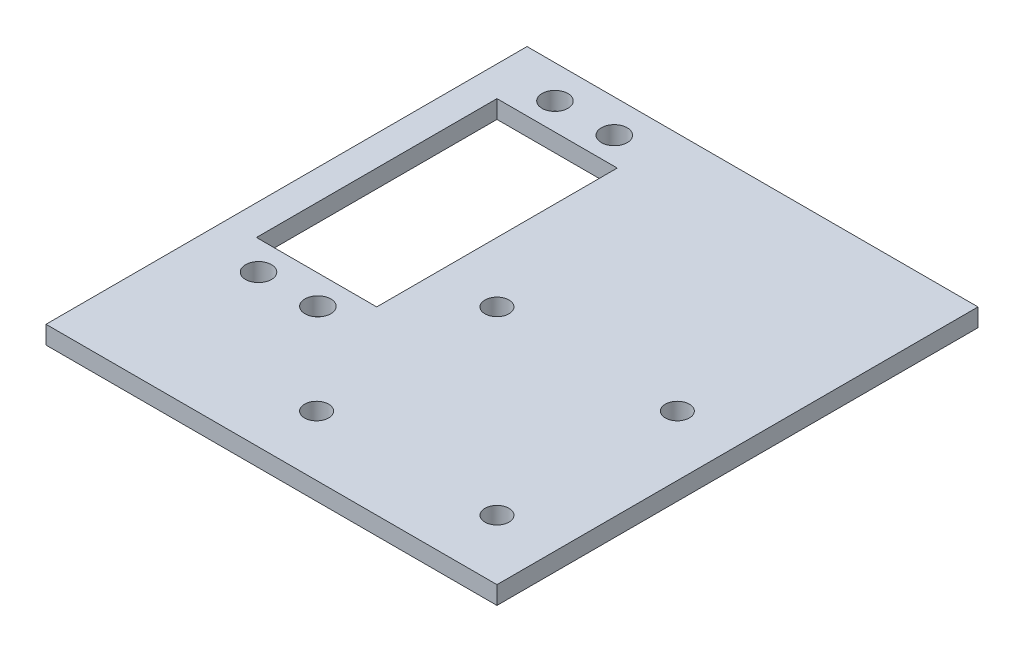
SolidWorks part; units mm, degrees
ref_plane "Front Plane" through (0, 0, 0) normal (0, 0, 1) x (1, 0, 0)
ref_plane "Top Plane" through (0, 0, 0) normal (0, 1, 0) x (1, 0, 0)
ref_plane "Right Plane" through (0, 0, 0) normal (1, 0, 0) x (0, 0, -1)
sketch "Sketch2" plane through (0, 0, 0) normal (0, 1, 0) x (1, 0, 0)
  line L1 (-40, -40) -> (40, -40)
  line L2 (-40, -40) -> (-40, 40)
  line L3 (-40, 40) -> (40, 40)
  line L4 (40, -40) -> (40, 40)
  line L5 (0, 40) -> (0, -40) construction
  line L6 (-40, 0) -> (40, 0) construction
  point P0 (0, 0)
  dimension "D1" = 80
  dimension "D2" = 80
extrude "Boss-Extrude1" add sketch "Sketch2" along normal blind 3
sketch "Sketch3" plane through (0, 3, 0) normal (0, 1, 0) x (1, 0, 0)
  line L0 (-35, 35) -> (-35, 40) construction
  line L2 (-40, 35) -> (-35, 35) construction
  line L3 (-40, 40) -> (-40, -40) construction
  line L5 (40, 40) -> (-40, 40) construction
  line L6 (-35, 35) -> (-30, 35) construction
  line L7 (-30, 35) -> (-30, 40) construction
  line L8 (-30, 35) -> (-20, 35) construction
  line L9 (-30, 35) -> (-30, 30) construction
  line L10 (-40, 30) -> (-35, 30) construction
  line L11 (-35, 30) -> (-15, 30) construction
  line L12 (-35, 30) -> (-35, -10) construction
  line L13 (-35, 10) -> (-15, 10) construction
  line L14 (-35, 30) -> (-15, 30)
  line L15 (-35, 30) -> (-35, -10)
  line L16 (-35, -10) -> (-15, -10)
  line L17 (-15, 30) -> (-15, -10)
  line L18 (-27.695, 34.49) -> (-31.995, 34.49) construction
  line L19 (-22.125, 34.49) -> (-17.825, 34.49) construction
  arc A4 (-31.05, 36.2706) -> (-28.64, 36.2706) centre (-29.845, 34.49) ccw construction
  arc A5 (-21.18, 36.2706) -> (-18.77, 36.2706) centre (-19.975, 34.49) ccw construction
  circle A6 centre (-29.845, 34.49) radius 2.15
  circle A7 centre (-19.975, 34.49) radius 2.15
  circle A8 centre (-19.975, -14.81) radius 2.15
  circle A9 centre (-29.845, -14.81) radius 2.15
  dimension "D4" = 10
  dimension "D5" = 5
  dimension "D1" = 5
  dimension "D2" = 5
  dimension "D3" = 5
  dimension "D6" = 20
  dimension "D7" = 40
extrude "Cut-Extrude1" cut sketch "Sketch3" against normal blind 3
sketch "Sketch4" plane through (0, 3, 0) normal (0, 1, 0) x (1, 0, 0)
  line L0 (-40, -40) -> (40, -40) construction
  line L1 (35, -40) -> (40, -40)
  line L2 (35, -40) -> (35, 40)
  line L3 (35, 40) -> (40, 40)
  line L4 (40, -40) -> (40, 40)
  line L5 (35, -170) -> (35, 10) construction
  line L6 (40, 40) -> (-40, 40) construction
  line L7 (40, -40) -> (40, 40) construction
extrude "Cut-Extrude2" cut sketch "Sketch4" against normal blind 10
sketch "Sketch5" plane through (0, 0, 0) normal (0, -1, 0) x (1, 0, 0)
  line L0 (10, -10) -> (10, 40) construction
  line L1 (35, -10) -> (-15, -10) construction
  line L2 (-40, 40) -> (35, 40) construction
  line L3 (35, 15) -> (-15, 15) construction
  line L4 (35, 40) -> (35, -40) construction
  line L5 (-15, -10) -> (-15, 170) construction
  line L6 (25, -10) -> (25, 40) construction
  line L7 (35, 0) -> (-15, 0) construction
  line L8 (-15, 10) -> (-15, -30) construction
  circle A0 centre (25, 0) radius 2
  circle A1 centre (-5, 0) radius 2
  circle A2 centre (-5, 30) radius 2
  circle A3 centre (25, 30) radius 2
  dimension "D1" = 10
  dimension "D2" = 10
extrude "Cut-Extrude3" cut sketch "Sketch5" against normal blind 10
